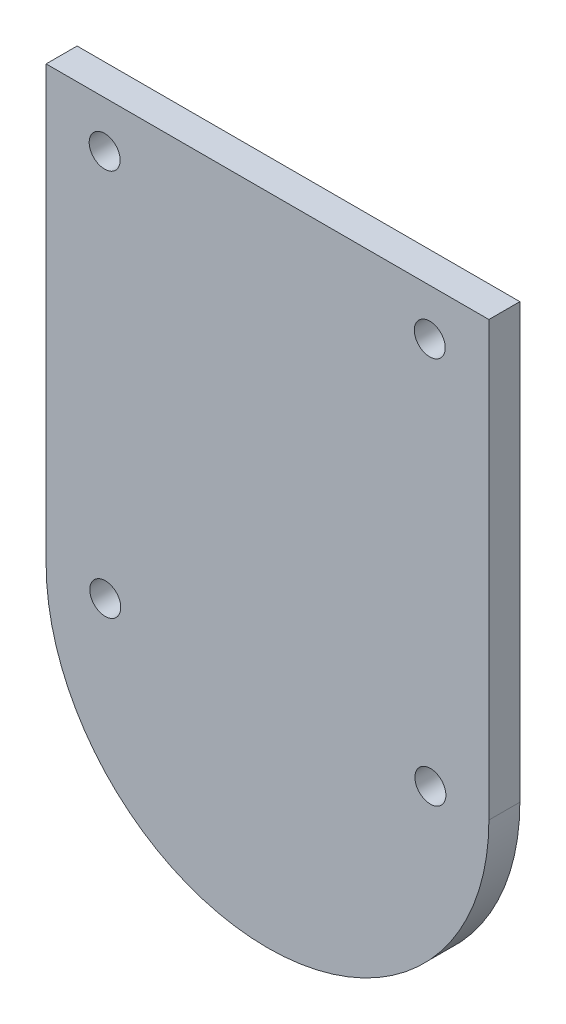
SolidWorks part; units mm, degrees
ref_plane "前视基准面" through (0, 0, 0) normal (0, 0, 1) x (1, 0, 0)
ref_plane "上视基准面" through (0, 0, 0) normal (0, 1, 0) x (1, 0, 0)
ref_plane "右视基准面" through (0, 0, 0) normal (1, 0, 0) x (0, 0, -1)
sketch "草图1" plane through (0, 0, 0) normal (0, 0, 1) x (1, 0, 0)
  line L0 (0, 24.3768) -> (28.6, 24.3768)
  line L27 (0, 24.3768) -> (0, -3.6232)
  line L28 (28.6, -3.6232) -> (28.6, 24.3768)
  circle A4 centre (24.78, 21.3768) radius 1
  arc A13 (0, -3.6232) -> (14.3, -17.9232) centre (14.3, -3.6232) ccw
  arc A14 (14.3, -17.9232) -> (28.6, -3.6232) centre (14.3, -3.6232) ccw
  circle A15 centre (3.78, 21.3768) radius 1
  circle A16 centre (3.82, -3.6232) radius 1
  circle A17 centre (24.82, -3.6232) radius 1
extrude "凸台-拉伸1" add sketch "草图1" along normal blind 2
